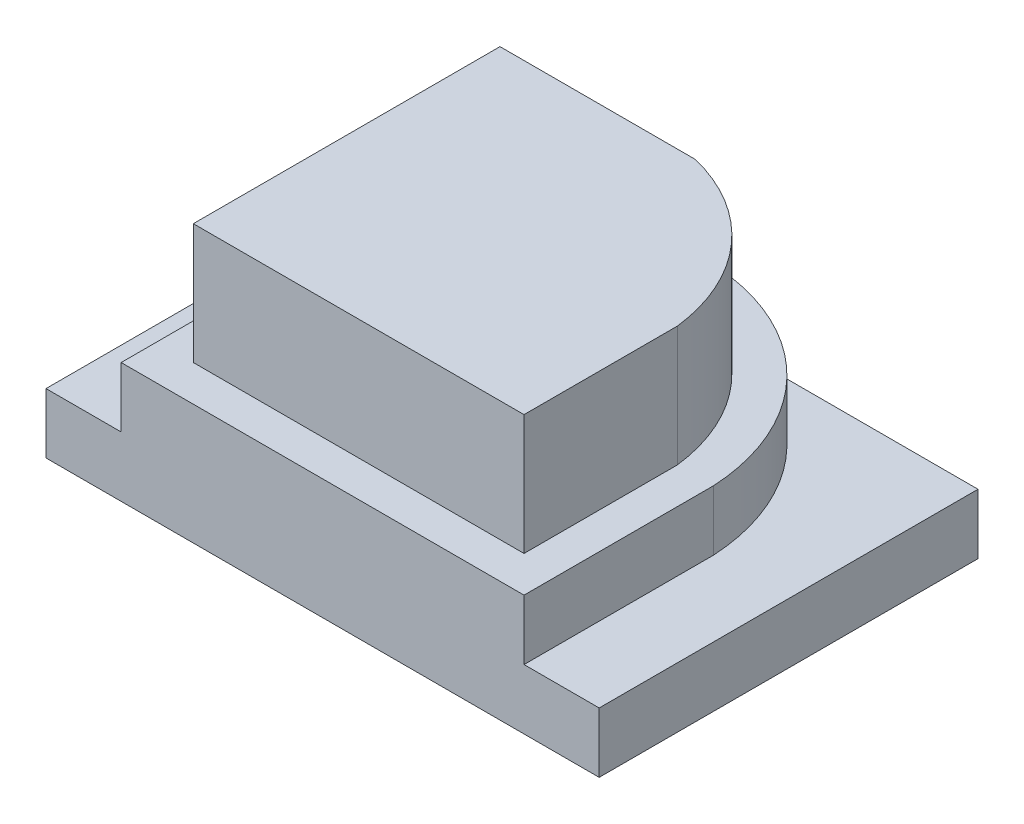
SolidWorks part; units mm, degrees
ref_plane "Front Plane" through (0, 0, 0) normal (0, 0, 1) x (1, 0, 0)
ref_plane "Top Plane" through (0, 0, 0) normal (0, 1, 0) x (1, 0, 0)
ref_plane "Right Plane" through (0, 0, 0) normal (1, 0, 0) x (0, 0, -1)
sketch "Sketch2" plane through (0, 0, 0) normal (0, 1, 0) x (1, 0, 0)
  line L0 (0, 2.8) -> (-6, 2.8) construction
  line L1 (0, 0) -> (-6, 0) construction
  line L2 (0, 0) -> (0, 2.8) construction
  line L3 (-2.5, 5.6) -> (-6, 5.6) construction
  line L4 (-6, 0) -> (-6, 5.6) construction
  line L5 (-6, 5.35) -> (-2.5, 5.35)
  line L6 (-0.25, 0) -> (-0.25, 2.5) construction
  line L7 (-6, 2.8) -> (-5.75, 2.8)
  line L8 (-5.75, 5.35) -> (-5.75, 0.25)
  line L9 (-5.75, 0.25) -> (-0.25, 0.25)
  line L10 (-0.25, 0.25) -> (-0.25, 2.8)
  arc A0 (0, 2.5) -> (-2.5, 5.6) centre (-2.9867, 2.6495) ccw construction
  arc A1 (-2.5, 5.35) -> (-0.25, 2.8) centre (-3.2196, 2.4474) cw
  dimension "D8" = 2.9904
  dimension "D9" = 2.9904
  dimension "D1" = 0.25
  dimension "D2" = 5.6
  dimension "D3" = 3.5
  dimension "D4" = 2.5
  dimension "D5" = 0.25
  dimension "D6" = 5.5
  dimension "D7" = 0.25
extrude "Boss-Extrude2" add sketch "Sketch2" along normal blind 2 contours A1 L5 L8 L9 L10
sketch "Sketch3" plane through (0, 0, 0) normal (0, -1, 0) x (1, 0, 0)
  line L0 (-6, 0) -> (-6, 0.35) construction
  line L1 (-6, 0) -> (-6.35, 0) construction
  line L2 (-6.35, 0.35) -> (0.35, 0.35)
  line L3 (0.35, 0.35) -> (0.35, -2.8)
  line L4 (-6.35, 0.35) -> (-6.35, -5.95)
  line L5 (-6.35, -5.95) -> (-2.5, -5.95)
  line L7 (0, 0) -> (0, -2.8) construction
  line L8 (-2.5, -5.6) -> (-6, -5.6) construction
  arc A0 (-2.5, -5.95) -> (0.35, -2.8) centre (-3.0099, -2.6244) ccw
  dimension "D4" = 3.85
  dimension "D5" = 3.15
  dimension "D1" = 0.35
  dimension "D2" = 0.35
  dimension "D3" = 0.35
  dimension "D6" = 0.35
extrude "Boss-Extrude3" add sketch "Sketch3" along normal blind 1
sketch "Sketch4" plane through (0, -1, 0) normal (0, -1, 0) x (1, 0, 0)
  line L0 (-6.35, 0.35) -> (-6.35, -5.95) construction
  line L1 (-7.6, 0.35) -> (1.6, 0.35)
  line L2 (-7.6, 0.35) -> (-7.6, -5.95)
  line L3 (-7.6, -5.95) -> (1.6, -5.95)
  line L4 (1.6, 0.35) -> (1.6, -5.95)
  line L5 (0.35, 0.35) -> (0.35, -2.8) construction
  point P10 (0, 0)
  dimension "D1" = 1.25
  dimension "D2" = 1.25
  dimension "D3" = 6.3
extrude "Boss-Extrude4" add sketch "Sketch4" along normal blind 1
